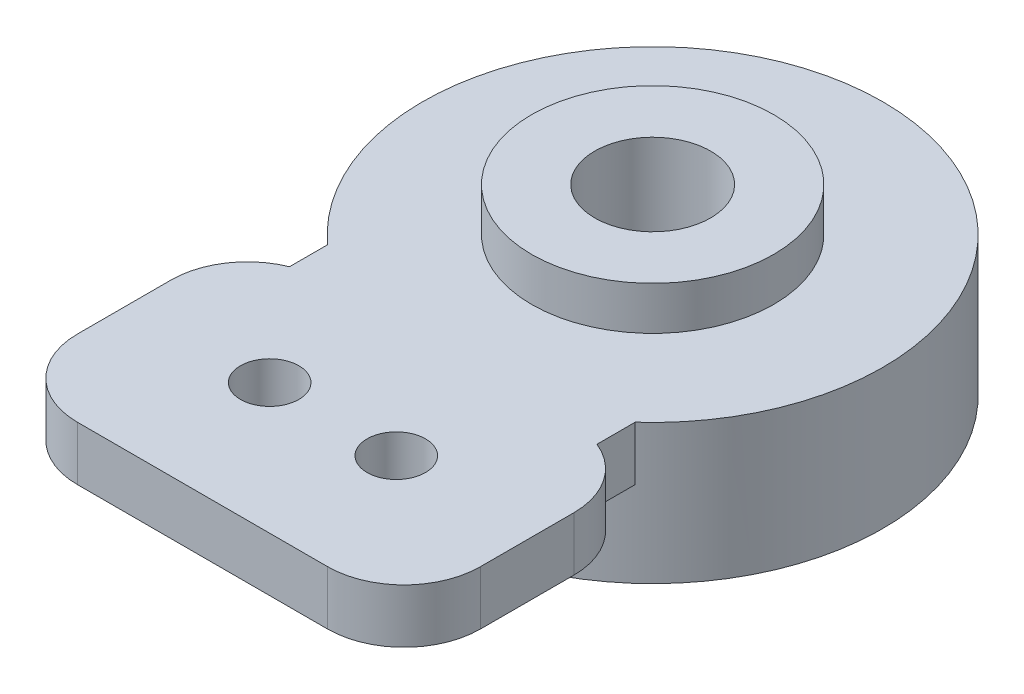
SolidWorks part; units mm, degrees
ref_plane "Front Plane" through (0, 0, 0) normal (0, 0, 1) x (1, 0, 0)
ref_plane "Top Plane" through (0, 0, 0) normal (0, 1, 0) x (1, 0, 0)
ref_plane "Right Plane" through (0, 0, 0) normal (1, 0, 0) x (0, 0, -1)
sketch "Sketch1" plane through (0, 0, 0) normal (0, 1, 0) x (1, 0, 0)
  line L0 (0, 0) -> (0, -17.1224) construction
  line L1 (-6.55, -23.57) -> (6.55, -23.57)
  line L2 (-10.55, -19.57) -> (-10.55, -14.6747)
  line L3 (-6.55, -14.6747) -> (6.55, -19.57) construction
  line L4 (10.55, -19.57) -> (10.55, -14.6747)
  line L5 (-6.55, -19.57) -> (6.55, -14.6747) construction
  line L7 (-25.1268, 12.05) -> (38.8699, 12.05) construction
  line L9 (-8.05, -8.9666) -> (-8.05, -10.9666)
  line L10 (8.05, -8.9666) -> (8.05, -10.9666)
  line L11 (-8.05, -9.9666) -> (8.05, -9.9666) construction
  arc A1 (8.05, -10.9666) -> (10.55, -14.6747) centre (6.55, -14.6747) cw
  arc A2 (6.55, -23.57) -> (10.55, -19.57) centre (6.55, -19.57) ccw
  arc A3 (-6.55, -23.57) -> (-10.55, -19.57) centre (-6.55, -19.57) cw
  arc A4 (-10.55, -14.6747) -> (-8.05, -10.9666) centre (-6.55, -14.6747) cw
  arc A5 (8.05, -8.9666) -> (-8.05, -8.9666) centre (0, 0) ccw
  point P3 (0, -17.1224)
  point P4 (0, -17.1224)
  point P5 (0, -17.1224)
  point P6 (0, -16.835)
  dimension "D1" = 12.05
  dimension "D5" = 4
  dimension "D2" = 35.62
  dimension "D3" = 21.1
  dimension "D6" = 16.1
  dimension "D7" = 2
extrude "Boss-Extrude1" add sketch "Sketch1" along normal blind 2.83
sketch "Sketch2" plane through (0, 0, 0) normal (0, -1, 0) x (1, 0, 0)
  circle A0 centre (0, 0) radius 12.05
  arc A1 (-8.05, 8.9666) -> (8.05, 8.9666) centre (0, 0) ccw construction
extrude "Boss-Extrude2" add sketch "Sketch2" along normal blind 4.48
sketch "Sketch3" plane through (0, 2.83, 0) normal (0, 1, 0) x (1, 0, 0)
  circle A0 centre (0, 0) radius 6.34
  dimension "D1" = 12.68
extrude "Boss-Extrude3" add sketch "Sketch3" along normal blind 2.27
sketch "Sketch4" plane through (0, 5.1, 0) normal (0, 1, 0) x (1, 0, 0)
  circle A0 centre (0, 0) radius 3.035
  dimension "D1" = 6.07
extrude "Cut-Extrude1" cut sketch "Sketch4" against normal through all
sketch "Sketch5" plane through (0, 2.83, 0) normal (0, 1, 0) x (1, 0, 0)
  line L0 (-6.55, -23.57) -> (6.55, -23.57) construction
  line L4 (-3.315, -18.27) -> (3.315, -18.27) construction
  line L5 (0, 0) -> (0, -23.57) construction
  line L6 (-3.315, -16.74) -> (3.315, -16.74) construction
  circle A0 centre (-3.315, -16.74) radius 1.53
  circle A1 centre (3.315, -16.74) radius 1.53
  point P3 (0, -16.74)
  dimension "D1" = 3.06
  dimension "D2" = 6.63
  dimension "D3" = 5.3
extrude "Cut-Extrude2" cut sketch "Sketch5" against normal through all
